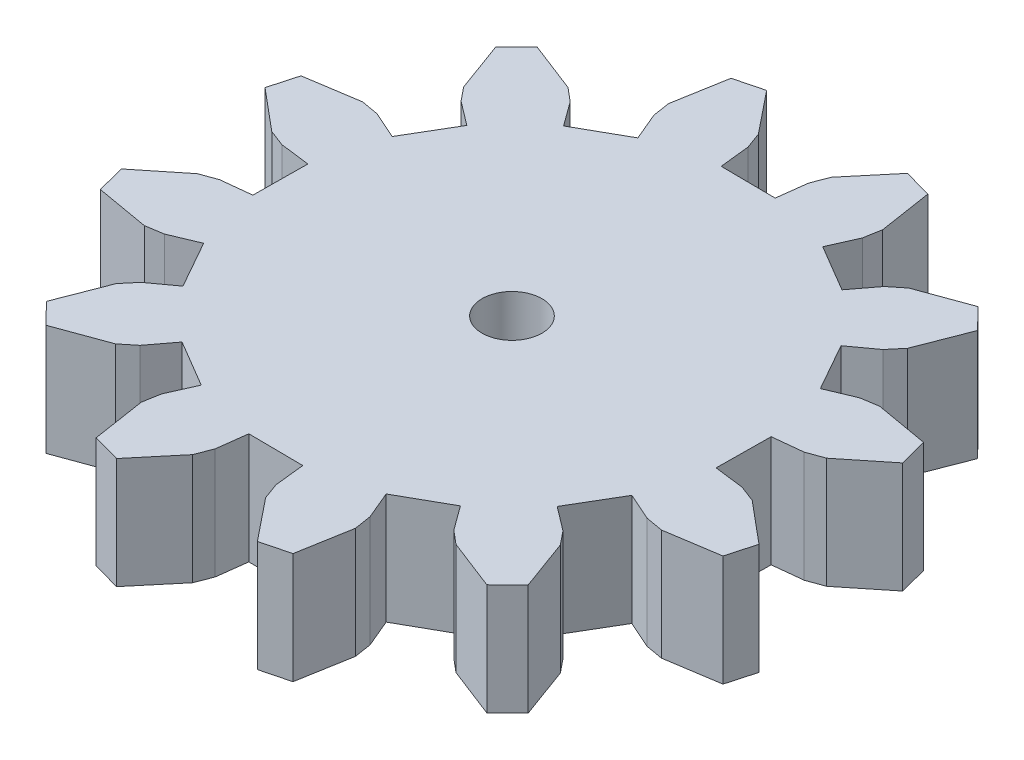
SolidWorks part; units mm, degrees
ref_plane "Front Plane" through (0, 0, 0) normal (0, 0, 1) x (1, 0, 0)
ref_plane "Top Plane" through (0, 0, 0) normal (0, 1, 0) x (1, 0, 0)
ref_plane "Right Plane" through (0, 0, 0) normal (1, 0, 0) x (0, 0, -1)
sketch "Sketch1" plane through (0, 0, 0) normal (0, 1, 0) x (1, 0, 0)
  line L0 (5.6453, 2.5628) -> (6.3944, 2.8777)
  line L1 (6.3944, 2.8777) -> (6.8624, 2.9509)
  line L2 (6.8624, 2.9509) -> (8.3004, 2.6996)
  line L3 (8.3004, 2.6996) -> (8.4975, 1.9343)
  line L4 (8.4975, 1.9343) -> (7.3599, 1.0196)
  line L5 (7.3599, 1.0196) -> (6.9147, 0.8576)
  line L6 (6.9147, 0.8576) -> (6.1067, 0.7714)
  line L7 (6.1067, 0.7714) -> (6.0924, -0.7021)
  line L8 (6.0924, -0.7021) -> (6.8985, -0.804)
  line L9 (6.8985, -0.804) -> (7.3405, -0.9746)
  line L10 (7.3405, -0.9746) -> (8.4602, -1.9112)
  line L11 (8.4602, -1.9112) -> (8.2482, -2.6725)
  line L12 (8.2482, -2.6725) -> (6.8057, -2.8958)
  line L13 (6.8057, -2.8958) -> (6.3391, -2.8135)
  line L14 (6.3391, -2.8135) -> (5.5963, -2.4842)
  line L15 (5.5963, -2.4842) -> (4.8472, -3.7531)
  line L16 (4.8472, -3.7531) -> (5.4944, -4.2444)
  line L17 (5.4944, -4.2444) -> (5.7918, -4.6132)
  line L18 (5.7918, -4.6132) -> (6.2932, -5.9841)
  line L19 (6.2932, -5.9841) -> (5.7289, -6.5375)
  line L20 (5.7289, -6.5375) -> (4.368, -6.0096)
  line L21 (4.368, -6.0096) -> (4.0051, -5.705)
  line L22 (4.0051, -5.705) -> (3.5265, -5.0484)
  line L23 (3.5265, -5.0484) -> (2.2432, -5.7728)
  line L24 (2.2432, -5.7728) -> (2.5581, -6.5219)
  line L25 (2.5581, -6.5219) -> (2.6313, -6.9899)
  line L26 (2.6313, -6.9899) -> (2.38, -8.4279)
  line L27 (2.38, -8.4279) -> (1.6147, -8.625)
  line L28 (1.6147, -8.625) -> (0.7, -7.4873)
  line L29 (0.7, -7.4873) -> (0.538, -7.0422)
  line L30 (0.538, -7.0422) -> (0.4518, -6.2342)
  line L31 (0.4518, -6.2342) -> (-1.0217, -6.2199)
  line L32 (-1.0217, -6.2199) -> (-1.1236, -7.026)
  line L33 (-1.1236, -7.026) -> (-1.2942, -7.468)
  line L34 (-1.2942, -7.468) -> (-2.2308, -8.5877)
  line L35 (-2.2308, -8.5877) -> (-2.9921, -8.3757)
  line L36 (-2.9921, -8.3757) -> (-3.2154, -6.9331)
  line L37 (-3.2154, -6.9331) -> (-3.1331, -6.4666)
  line L38 (-3.1331, -6.4666) -> (-2.8038, -5.7238)
  line L39 (-2.8038, -5.7238) -> (-4.0727, -4.9747)
  line L40 (-4.0727, -4.9747) -> (-4.564, -5.6218)
  line L41 (-4.564, -5.6218) -> (-4.9328, -5.9193)
  line L42 (-4.9328, -5.9193) -> (-6.3037, -6.4207)
  line L43 (-6.3037, -6.4207) -> (-6.8571, -5.8564)
  line L44 (-6.8571, -5.8564) -> (-6.3292, -4.4955)
  line L45 (-6.3292, -4.4955) -> (-6.0246, -4.1326)
  line L46 (-6.0246, -4.1326) -> (-5.368, -3.654)
  line L47 (-5.368, -3.654) -> (-6.0924, -2.3707)
  line L48 (-6.0924, -2.3707) -> (-6.8415, -2.6856)
  line L49 (-6.8415, -2.6856) -> (-7.3095, -2.7588)
  line L50 (-7.3095, -2.7588) -> (-8.7475, -2.5075)
  line L51 (-8.7475, -2.5075) -> (-8.9446, -1.7422)
  line L52 (-8.9446, -1.7422) -> (-7.807, -0.8275)
  line L53 (-7.807, -0.8275) -> (-7.3618, -0.6655)
  line L54 (-7.3618, -0.6655) -> (-6.5538, -0.5793)
  line L55 (-6.5538, -0.5793) -> (-6.5395, 0.8942)
  line L56 (-6.5395, 0.8942) -> (-7.3456, 0.9961)
  line L57 (-7.3456, 0.9961) -> (-7.7876, 1.1667)
  line L58 (-7.7876, 1.1667) -> (-8.9073, 2.1033)
  line L59 (-8.9073, 2.1033) -> (-8.6953, 2.8646)
  line L60 (-8.6953, 2.8646) -> (-7.2528, 3.0879)
  line L61 (-7.2528, 3.0879) -> (-6.7862, 3.0056)
  line L62 (-6.7862, 3.0056) -> (-6.0434, 2.6763)
  line L63 (-6.0434, 2.6763) -> (-5.2943, 3.9452)
  line L64 (-5.2943, 3.9452) -> (-5.9415, 4.4365)
  line L65 (-5.9415, 4.4365) -> (-6.2389, 4.8053)
  line L66 (-6.2389, 4.8053) -> (-6.7403, 6.1762)
  line L67 (-6.7403, 6.1762) -> (-6.176, 6.7296)
  line L68 (-6.176, 6.7296) -> (-4.8151, 6.2017)
  line L69 (-4.8151, 6.2017) -> (-4.4522, 5.8971)
  line L70 (-4.4522, 5.8971) -> (-3.9736, 5.2405)
  line L71 (-3.9736, 5.2405) -> (-2.6903, 5.9649)
  line L72 (-2.6903, 5.9649) -> (-3.0052, 6.714)
  line L73 (-3.0052, 6.714) -> (-3.0784, 7.182)
  line L74 (-3.0784, 7.182) -> (-2.8271, 8.62)
  line L75 (-2.8271, 8.62) -> (-2.0618, 8.8171)
  line L76 (-2.0618, 8.8171) -> (-1.1471, 7.6795)
  line L77 (-1.1471, 7.6795) -> (-0.9851, 7.2343)
  line L78 (-0.9851, 7.2343) -> (-0.8989, 6.4263)
  line L79 (-0.8989, 6.4263) -> (0.5746, 6.412)
  line L80 (0.5746, 6.412) -> (0.6765, 7.2181)
  line L81 (0.6765, 7.2181) -> (0.8471, 7.6601)
  line L82 (0.8471, 7.6601) -> (1.7837, 8.7798)
  line L83 (1.7837, 8.7798) -> (2.545, 8.5678)
  line L84 (2.545, 8.5678) -> (2.7683, 7.1253)
  line L85 (2.7683, 7.1253) -> (2.686, 6.6587)
  line L86 (2.686, 6.6587) -> (2.3567, 5.9159)
  line L87 (2.3567, 5.9159) -> (3.6256, 5.1668)
  line L88 (3.6256, 5.1668) -> (4.1169, 5.814)
  line L89 (4.1169, 5.814) -> (4.4857, 6.1114)
  line L90 (4.4857, 6.1114) -> (5.8566, 6.6128)
  line L91 (5.8566, 6.6128) -> (6.41, 6.0486)
  line L92 (6.41, 6.0486) -> (5.8821, 4.6876)
  line L93 (5.8821, 4.6876) -> (5.5775, 4.3247)
  line L94 (5.5775, 4.3247) -> (4.9209, 3.8461)
  line L95 (4.9209, 3.8461) -> (5.6453, 2.5628)
  line L96 (-6.5467, 0.1574) -> (6.0996, 0.0347) construction
  circle A0 centre (-0.2235, 0.0961) radius 0.81
  point P102 (-6.5467, 0.1574)
  point P103 (6.0996, 0.0347)
  dimension "D1" = 1.62
  dimension "D2" = 12.6462
extrude "Boss-Extrude1" add sketch "Sketch1" along normal blind 3
